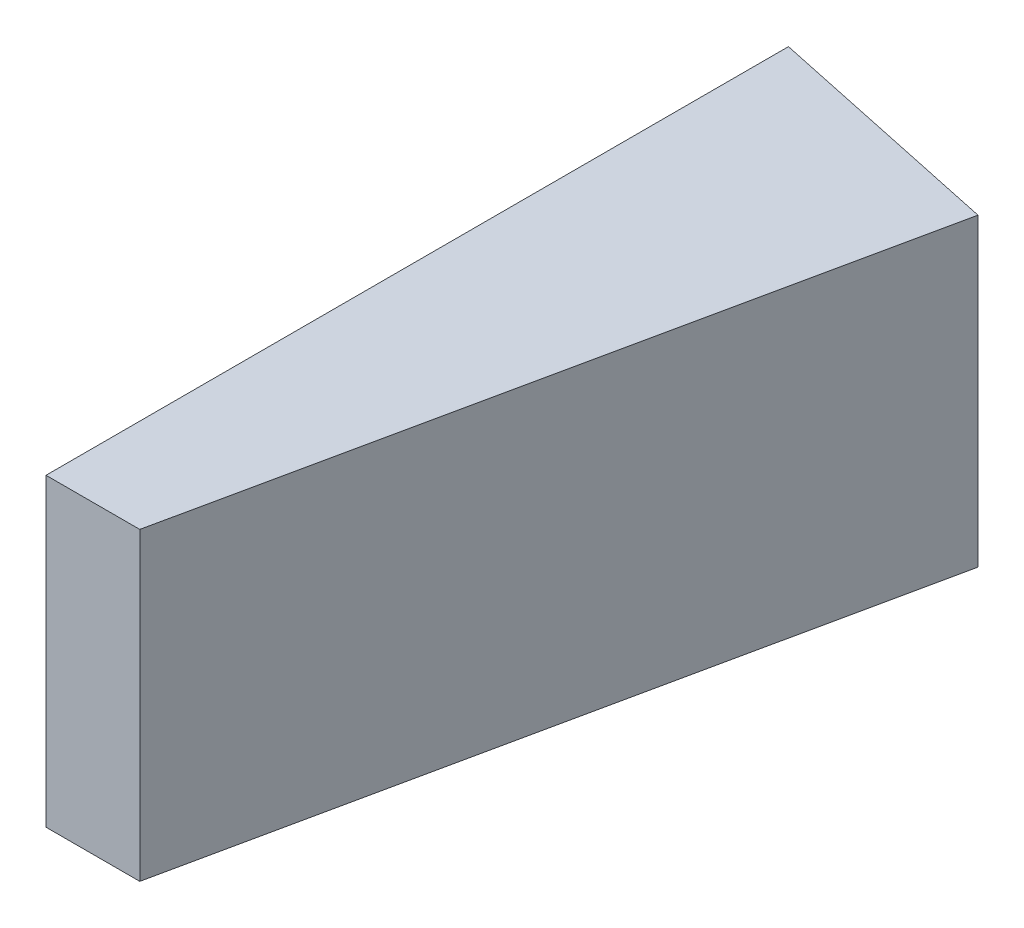
SolidWorks part; units mm, degrees
ref_plane "Front Plane" through (0, 0, 0) normal (0, 0, 1) x (1, 0, 0)
ref_plane "Top Plane" through (0, 0, 0) normal (0, 1, 0) x (1, 0, 0)
ref_plane "Right Plane" through (0, 0, 0) normal (1, 0, 0) x (0, 0, -1)
sketch "Sketch1" plane through (0, 0, 0) normal (0, 1, 0) x (1, 0, 0)
  line L0 (0, 0) -> (0, 24.3577)
  line L1 (0, 24.3577) -> (7.8977, 22.679)
  line L3 (0, 0) -> (3.0771, 0)
  line L4 (3.0771, 0) -> (7.8977, 22.679)
  point P3 (0, 0)
  point P6 (0, 24.3577)
  point P8 (11.3148, 20.3889)
  dimension "D1" = 102
extrude "Boss-Extrude1" add sketch "Sketch1" along normal blind 10
